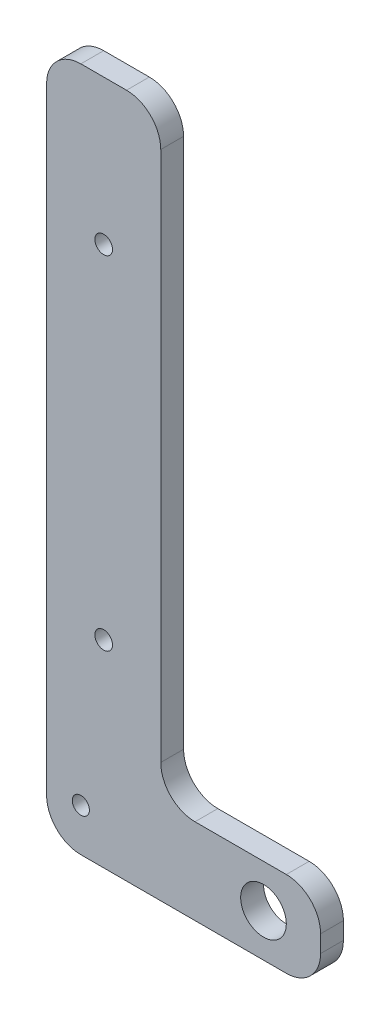
SolidWorks part; units mm, degrees
ref_plane "Front Plane" through (0, 0, 0) normal (0, 0, 1) x (1, 0, 0)
ref_plane "Top Plane" through (0, 0, 0) normal (0, 1, 0) x (1, 0, 0)
ref_plane "Right Plane" through (0, 0, 0) normal (1, 0, 0) x (0, 0, -1)
sketch "Sketch1" plane through (0, 0, 0) normal (0, 0, 1) x (1, 0, 0)
  line L0 (0, 0) -> (14, 0) construction
  line L1 (-24, 7.5) -> (24, 7.5)
  line L2 (-24, 7.5) -> (-24, -7.5)
  line L3 (-24, -7.5) -> (24, -7.5)
  line L4 (24, 7.5) -> (24, -7.5)
  line L5 (-24, 7.5) -> (24, -7.5) construction
  line L6 (-24, -7.5) -> (24, 7.5) construction
  line L7 (-24, -7.5) -> (-4, -7.5)
  line L8 (-24, -7.5) -> (-24, 112.5)
  line L9 (-24, 112.5) -> (-4, 112.5)
  line L10 (-4, -7.5) -> (-4, 112.5)
  line L11 (-14, 112.5) -> (-14, 7.5) construction
  circle A2 centre (14, 0) radius 4
  circle A9 centre (-18, 0) radius 1.5
  circle A10 centre (-14, 87.1) radius 1.55
  circle A11 centre (-14, 27.1) radius 1.55
  point P0 (0, 0)
  point P20 (-14, 27.6596)
  point P21 (-14, 87.1)
  dimension "D5" = 8
  dimension "D6" = 32
  dimension "D8" = 3
  dimension "D12" = 3.1
  dimension "D1" = 48
  dimension "D2" = 15
  dimension "D3" = 120
  dimension "D4" = 20
  dimension "D7" = 7.5
  dimension "D9" = 10
  dimension "D10" = 60
  dimension "D11" = 25.4
extrude "Boss-Extrude1" add sketch "Sketch1" along normal mid plane 4
fillet "Fillet1" radius 6 6 edges at (-4, 112.5, 0) (-24, 112.5, 0) (-24, -7.5, 0) (24, 7.5, 0) (-4, 7.5, 0) (24, -7.5, 0)
